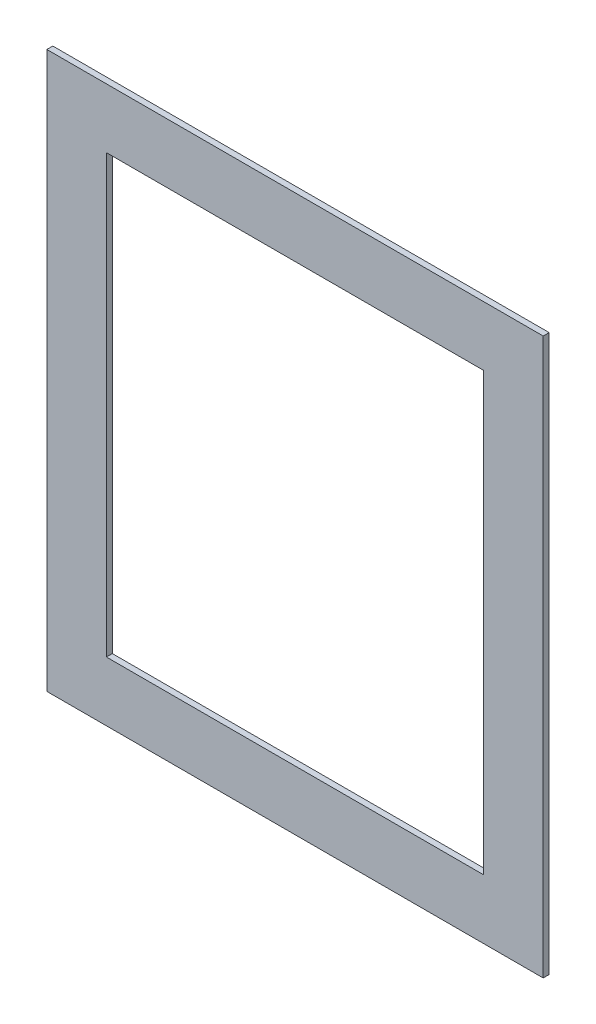
SolidWorks part; units mm, degrees
material "Клен"
ref_plane "Спереди" through (0, 0, 0) normal (0, 0, 1) x (1, 0, 0)
ref_plane "Сверху" through (0, 0, 0) normal (0, 1, 0) x (1, 0, 0)
ref_plane "Справа" through (0, 0, 0) normal (1, 0, 0) x (0, 0, -1)
sketch "Эскиз1" plane through (0, 0, 0) normal (0, 0, 1) x (1, 0, 0)
  line L0 (-1.6498, 480.4642) -> (-1.6498, 40.4642)
  line L1 (-61.6498, 540.4642) -> (438.3502, 540.4642)
  line L2 (-61.6498, 540.4642) -> (-61.6498, -19.5358)
  line L3 (-61.6498, -19.5358) -> (438.3502, -19.5358)
  line L4 (438.3502, 540.4642) -> (438.3502, -19.5358)
  line L5 (-1.6498, 40.4642) -> (378.3502, 40.4642)
  line L6 (378.3502, 480.4642) -> (378.3502, 40.4642)
  line L7 (-1.6498, 480.4642) -> (378.3502, 480.4642)
  dimension "D1" = 560
  dimension "D2" = 500
  dimension "D3" = 60
extrude "Бобышка-Вытянуть1" add sketch "Эскиз1" along normal blind 6
equation "\"D1@Эскиз1\"=500+60"
